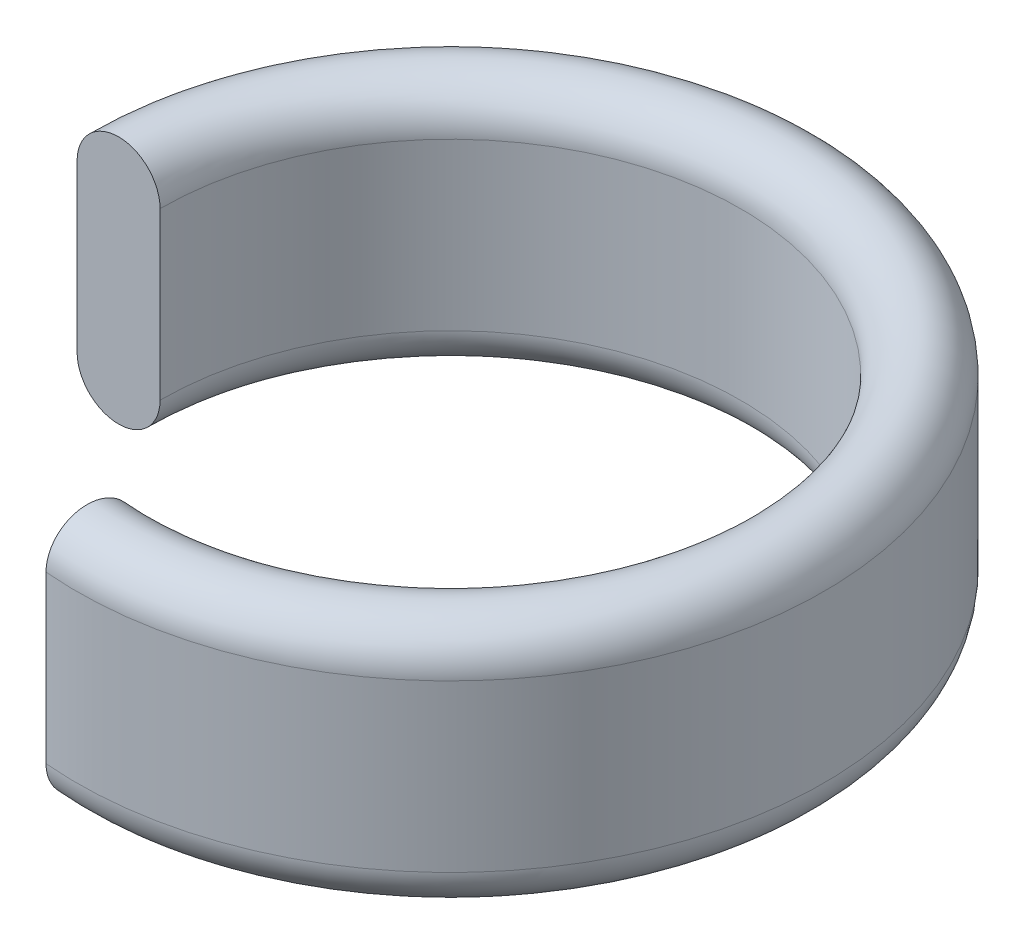
SolidWorks part; units mm, degrees
ref_plane "Front Plane" through (0, 0, 0) normal (0, 0, 1) x (1, 0, 0)
ref_plane "Top Plane" through (0, 0, 0) normal (0, 1, 0) x (1, 0, 0)
ref_plane "Right Plane" through (0, 0, 0) normal (1, 0, 0) x (0, 0, -1)
sketch "Sketch1" plane through (0, 0, 0) normal (0, 0, 1) x (1, 0, 0)
  line L0 (0, 8.7573) -> (0, -12.1558) construction
  line L3 (-20, -7.7886) -> (-20, 17.7886) construction
  line L4 (-22.5, -5) -> (-22.5, 5)
  line L5 (-17.5, -5) -> (-17.5, 5)
  arc A2 (-22.5, 5) -> (-17.5, 5) centre (-20, 5) cw
  arc A3 (-17.5, -5) -> (-22.5, -5) centre (-20, -5) cw
  point P3 (-17.5, 0)
  dimension "D6" = 10
  dimension "D4" = 20
  dimension "D5" = 2.5
revolve "Revolve1" add sketch "Sketch1" angle 275 about L0
ref_plane "Plane1" through (0, 0, 0) normal (0.7071, 0, -0.7071) x (-0.7071, 0, -0.7071)
ref_plane "Plane2" through (21.2132, 0, -21.2132) normal (0.7071, 0, -0.7071) x (-0.7071, 0, -0.7071)
